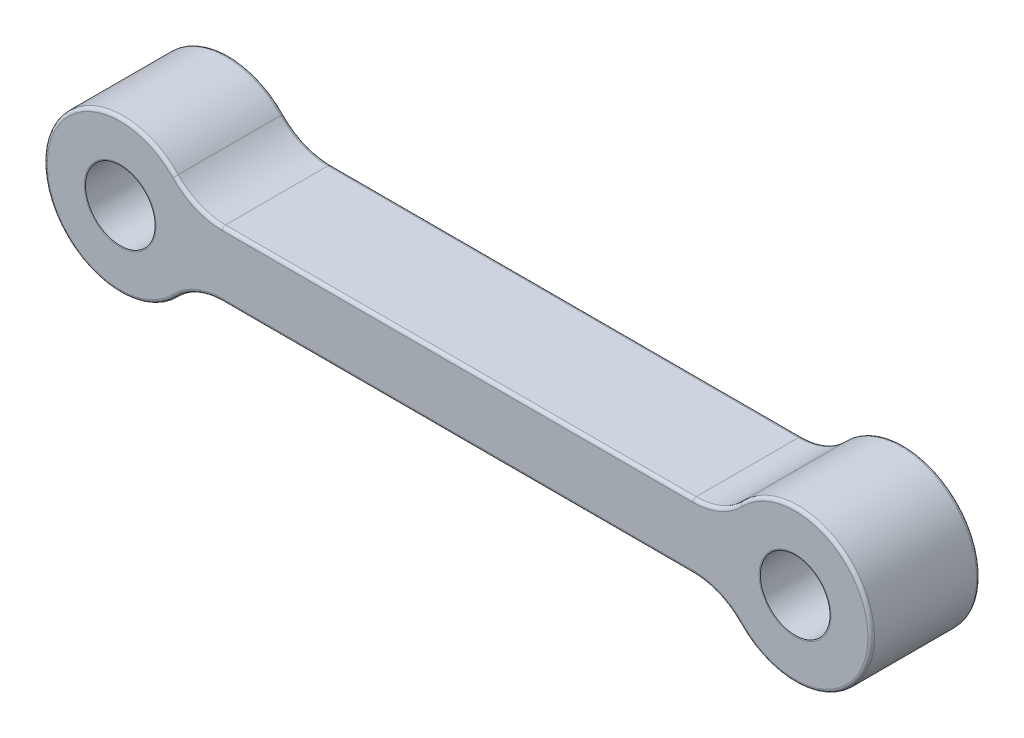
SolidWorks part; units mm, degrees
ref_plane "Front Plane" through (0, 0, 0) normal (0, 0, 1) x (1, 0, 0)
ref_plane "Top Plane" through (0, 0, 0) normal (0, 1, 0) x (1, 0, 0)
ref_plane "Right Plane" through (0, 0, 0) normal (1, 0, 0) x (0, 0, -1)
sketch "Sketch1" plane through (0, 0, 0) normal (0, 0, 1) x (1, 0, 0)
  line L0 (0, 0) -> (31, 0) construction
  line L1 (0, 3.5) -> (31, 3.5) construction
  line L2 (0, -3.5) -> (31, -3.5) construction
  line L3 (15.5, 0) -> (15.5, -3.5) construction
  line L5 (27.8377, -1.5) -> (3.1623, -1.5)
  line L6 (27.8377, -1.5) -> (27.8377, 1.5) construction
  line L7 (27.8377, 1.5) -> (3.1623, 1.5)
  line L8 (3.1623, -1.5) -> (3.1623, 1.5) construction
  line L9 (27.8377, -1.5) -> (3.1623, 1.5) construction
  line L10 (27.8377, 1.5) -> (3.1623, -1.5) construction
  arc A0 (0, 3.5) -> (0, -3.5) centre (0, 0) ccw construction
  arc A1 (31, -3.5) -> (31, 3.5) centre (31, 0) ccw construction
  circle A2 centre (0, 0) radius 1.5
  circle A3 centre (0, 0) radius 3.5
  circle A4 centre (31, 0) radius 1.5
  circle A5 centre (31, 0) radius 3.5
  point P3 (15.5, 0)
  dimension "D3" = 3
  dimension "D1" = 31
  dimension "D2" = 7
  dimension "D4" = 3
extrude "Boss-Extrude1" add sketch "Sketch1" along normal mid plane 5 contours A3 A2 | L5 A5 L7 A3 | A5 A4
fillet "Fillet1" radius 3 4 edges at (3.1623, 1.5, 0) (27.8377, 1.5, 0) (3.1623, -1.5, 0) (27.8377, -1.5, 0)
fillet "Fillet2" radius 0.15 20 edges at (32.5, 0, -2.5) (1.5, 0, -2.5) (3.5137, 1.7404, -2.5) (-3.5, 0, -2.5) (3.5137, -1.7404, -2.5) (15.5, -1.5, -2.5) (27.4863, -1.7404, -2.5) (34.5, 0, -2.5) (27.4863, 1.7404, -2.5) (15.5, 1.5, -2.5) (32.5, 0, 2.5) (1.5, 0, 2.5) (27.4863, -1.7404, 2.5) (15.5, -1.5, 2.5) (3.5137, -1.7404, 2.5) (-3.5, 0, 2.5) (3.5137, 1.7404, 2.5) (15.5, 1.5, 2.5) (27.4863, 1.7404, 2.5) (34.5, 0, 2.5)
hole_wizard "M3 Clearance Hole1" positions "Sketch2" profile "Sketch3" hole size "M3" standard "ANSI Metric" end condition through all
sketch "Sketch2" plane through (0, 0, -2.5) normal (0, 0, -1) x (-1, 0, 0)
  point P0 (-31, 0)
  point P3 (0, 0)
sketch "Sketch3" plane through (31, 0, -2.5) normal (1, 0, 0) x (0, 1, 0)
  line L0 (0, 0) -> (0, 5)
  line L1 (0, 5) -> (1.6, 5)
  line L2 (1.6, 5) -> (1.6, 0)
  line L5 (1.6, 0) -> (0, 0)
  line L11 (0, -6.35) -> (0, 107.95) construction
  dimension "Thru Hole Dia." = 3.2
  dimension "Thru Hole Depth" = 5
